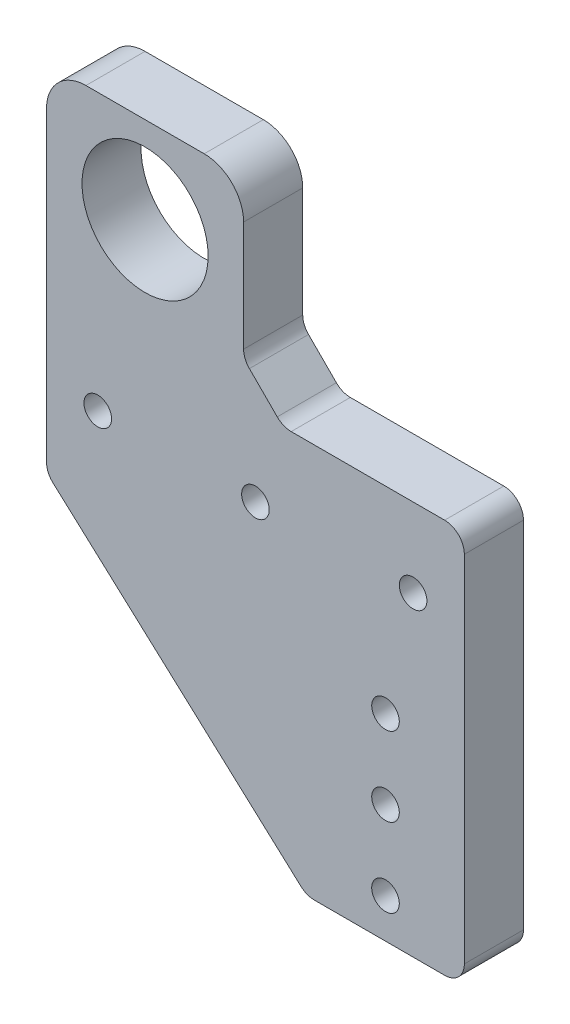
SolidWorks part; units mm, degrees
ref_plane "Front" through (0, 0, 0) normal (0, 0, 1) x (1, 0, 0)
ref_plane "Top" through (0, 0, 0) normal (0, 1, 0) x (1, 0, 0)
ref_plane "Right" through (0, 0, 0) normal (1, 0, 0) x (0, 0, -1)
sketch "Esquisse1" plane through (0, 0, 0) normal (0, 0, 1) x (1, 0, 0)
  line L0 (0, 0) -> (0, 100)
  line L1 (0, 100) -> (-106, 100)
  line L2 (-106, 100) -> (-106, 60)
  line L3 (-106, 60) -> (-40, 0)
  line L4 (-40, 0) -> (0, 0)
  dimension "D1" = 40
  dimension "D2" = 40
  dimension "D3" = 106
  dimension "D4" = 100
extrude "Boss.-Extru.1" add sketch "Esquisse1" along normal blind 15
sketch "Esquisse2" plane through (0, 0, 15) normal (0, 0, 1) x (1, 0, 0)
  line L0 (-20, 0) -> (-20, 100) construction
  line L1 (-40, 0) -> (0, 0) construction
  line L2 (0, 100) -> (-106, 100) construction
  line L3 (-106, 80) -> (0, 80) construction
  line L4 (-106, 100) -> (-106, 60) construction
  line L5 (0, 0) -> (0, 100) construction
  line L6 (-53, 80) -> (-53, 100) construction
  circle A0 centre (-20, 10) radius 3.5
  circle A1 centre (-20, 30) radius 3.5
  circle A2 centre (-20, 50) radius 3.5
  circle A3 centre (-53, 80) radius 3.5
  circle A4 centre (-93, 80) radius 3.5
  circle A5 centre (-13, 80) radius 3.5
  dimension "D1" = 20
  dimension "D2" = 20
  dimension "D3" = 7
  dimension "D4" = 10
  dimension "D5" = 40
  dimension "D6" = 7
extrude "Enlèv. mat.-Extru.1" cut sketch "Esquisse2" against normal through all both and the other way through all
sketch "Esquisse3" plane through (0, 0, 15) normal (0, 0, 1) x (1, 0, 0)
  line L1 (-106, 100) -> (-56, 100)
  line L2 (-106, 100) -> (-106, 150)
  line L3 (-106, 150) -> (-56, 150)
  line L4 (-56, 100) -> (-56, 150)
  dimension "D1" = 50
  dimension "D2" = 50
extrude "Boss.-Extru.2" add sketch "Esquisse3" against normal up to vertex (15 mm away) up to point (0, 100, 0)
chamfer "Chanfrein1" distance 10 angle 45 1 edges at (-56, 100, 7.5)
sketch "Esquisse4" plane through (0, 0, 15) normal (0, 0, 1) x (1, 0, 0)
  line L0 (-81, 150) -> (-81, 128) construction
  line L1 (-56, 150) -> (-106, 150) construction
  circle A0 centre (-81, 128) radius 16
  dimension "D1" = 32
  dimension "D2" = 22
extrude "Enlèv. mat.-Extru.2" cut sketch "Esquisse4" against normal through all both and the other way through all
sketch "Esquisse5" [suppressed] plane through (0, 0, 15) normal (0, 0, 1) x (1, 0, 0)
  circle A0 centre (-81, 128) radius 42
  circle A1 centre (-81, 128) radius 20
  dimension "D1" = 84
  dimension "D2" = 40
extrude "Boss.-Extru.3" [suppressed] add sketch "Esquisse5" against normal up to vertex
sketch "Esquisse6" [suppressed] plane through (0, 0, 15) normal (0, 0, 1) x (1, 0, 0)
  line L0 (-45, 128) -> (-81, 128) construction
  line L1 (-81, 128) -> (-99, 159.1769) construction
  line L2 (-99, 96.8231) -> (-81, 128) construction
  circle A0 centre (-81, 128) radius 36 construction
  circle A2 centre (-99, 159.1769) radius 3.5
  circle A3 centre (-99, 96.8231) radius 3.5
  circle A4 centre (-45, 128) radius 3.5
  dimension "D1" = 72
  dimension "D4" = 7
  dimension "D2" = 120
  dimension "D3" = 120
extrude "Enlèv. mat.-Extru.4" [suppressed] cut sketch "Esquisse6" against normal through all both and the other way through all
sketch "Esquisse7" [suppressed] plane through (0, 0, 15) normal (0, 0, 1) x (1, 0, 0)
  line L0 (-41, 100) -> (-45.2913, 105.8892)
  line L1 (0, 100) -> (-46, 100) construction
  line L2 (-45.2913, 105.8892) -> (-53.3733, 100)
  line L3 (-53.3733, 100) -> (-41, 100)
  arc A0 (-48.0085, 102.0085) -> (-106, 94.2509) centre (-81, 128) ccw construction
  dimension "D1" = 5
  dimension "D2" = 10
extrude "Boss.-Extru.4" [suppressed] add sketch "Esquisse7" against normal up to vertex
fillet "Congé1" [suppressed] radius 5
fillet "Congé2" radius 5 6 edges at (-56, 110, 7.5) (-46, 100, 7.5) (0, 100, 7.5) (0, 0, 7.5) (-40, 0, 7.5) (-106, 60, 7.5)
fillet "Congé3" radius 10 2 edges at (-106, 150, 7.5) (-56, 150, 7.5)
